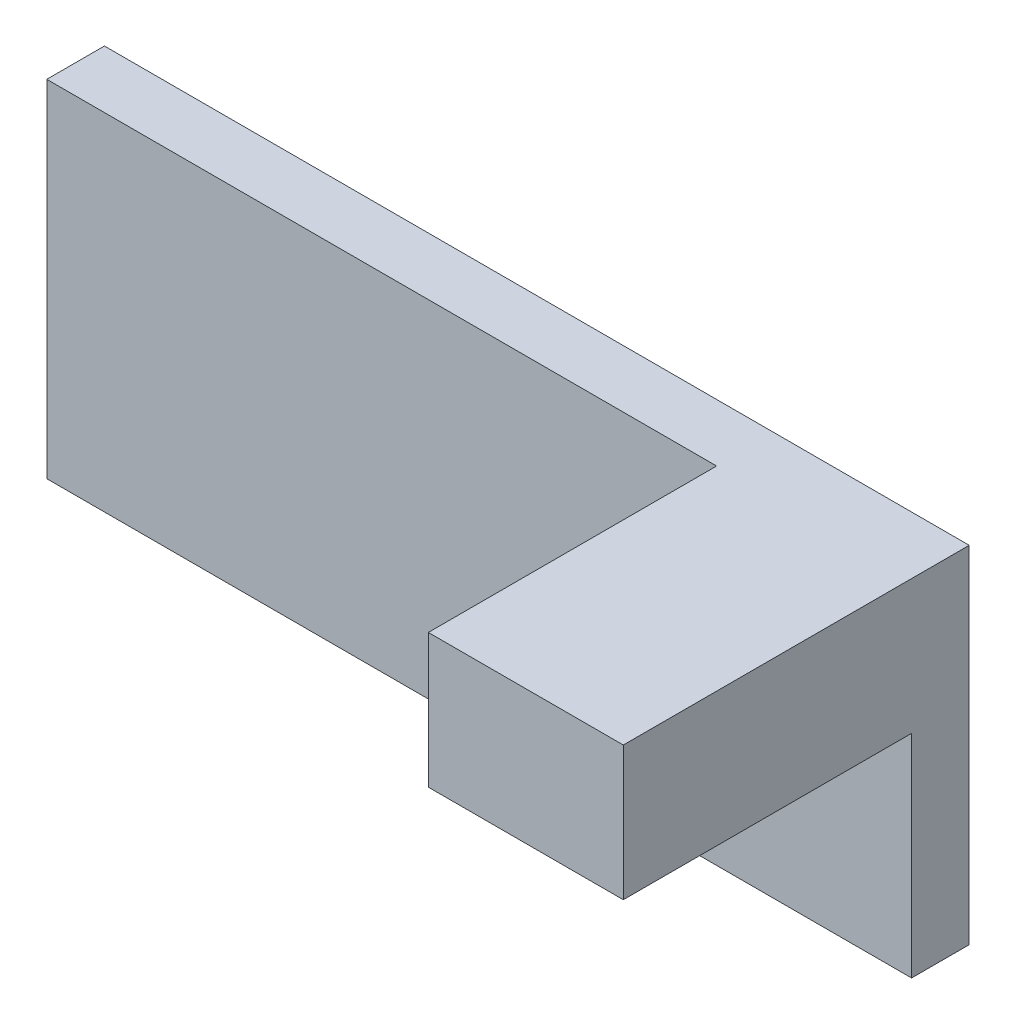
SolidWorks part; units mm, degrees
ref_plane "前视基准面" through (0, 0, 0) normal (0, 0, 1) x (1, 0, 0)
ref_plane "上视基准面" through (0, 0, 0) normal (0, 1, 0) x (1, 0, 0)
ref_plane "右视基准面" through (0, 0, 0) normal (1, 0, 0) x (0, 0, -1)
sketch "草图3" plane through (0, 0, 0) normal (0, 0, 1) x (1, 0, 0)
  line L1 (-75, -30) -> (75, -30)
  line L2 (-75, -30) -> (-75, 30)
  line L3 (-75, 30) -> (75, 30)
  line L4 (75, -30) -> (75, 30)
  line L5 (-75, -30) -> (75, 30) construction
  line L6 (-75, 30) -> (75, -30) construction
  point P0 (0, 0)
  dimension "D1" = 150
  dimension "D2" = 60
extrude "凸台-拉伸3" add sketch "草图3" along normal blind 10
sketch "草图4" plane through (0, 0, 10) normal (0, 0, 1) x (1, 0, 0)
  line L1 (41.1839, 6.7543) -> (75, 6.7543)
  line L2 (41.1839, 6.7543) -> (41.1839, 30)
  line L3 (41.1839, 30) -> (75, 30)
  line L4 (75, 6.7543) -> (75, 30)
  line L5 (41.1839, 6.7543) -> (75, 30) construction
  line L6 (41.1839, 30) -> (75, 6.7543) construction
  point P0 (58.092, 18.3772)
extrude "凸台-拉伸4" add sketch "草图4" along normal blind 50
